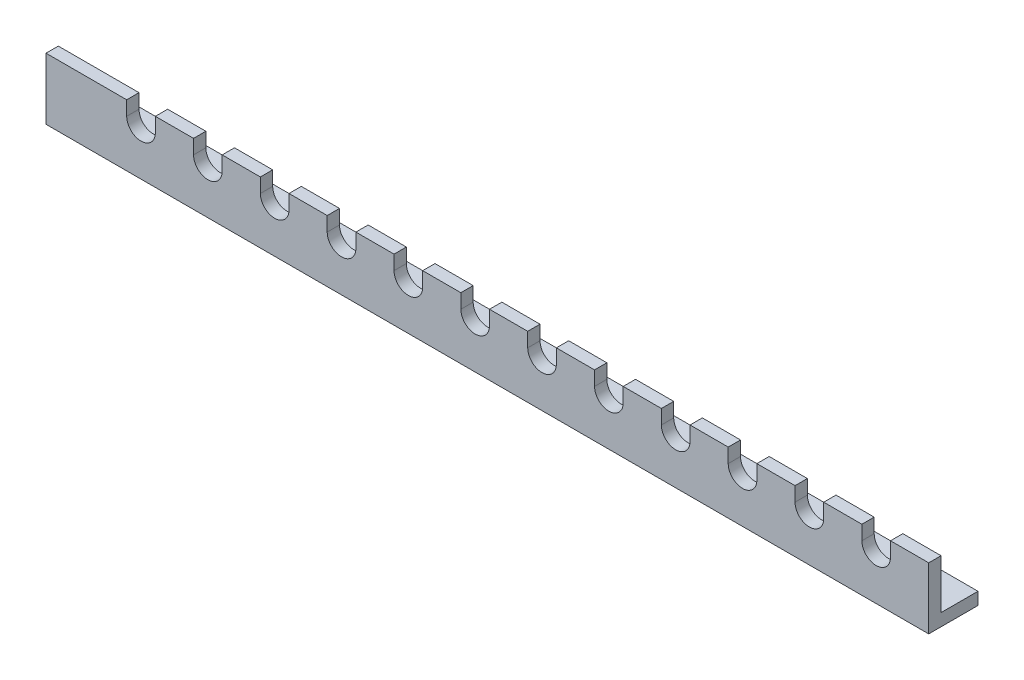
SolidWorks part; units mm, degrees
ref_plane "Front" through (0, 0, 0) normal (0, 0, 1) x (1, 0, 0)
ref_plane "Top" through (0, 0, 0) normal (0, 1, 0) x (1, 0, 0)
ref_plane "Right" through (0, 0, 0) normal (1, 0, 0) x (0, 0, -1)
sketch "Sketch1" plane through (0, 0, 0) normal (0, 0, 1) x (1, 0, 0)
  line L0 (-4.65, 0) -> (-4.65, 4.65)
  line L1 (4.65, 0) -> (4.65, 4.65)
  line L2 (4.65, 4.65) -> (17.05, 4.65)
  line L3 (17.05, 0) -> (17.05, 4.65)
  line L4 (26.35, 0) -> (26.35, 4.65)
  line L5 (26.35, 4.65) -> (38.75, 4.65)
  line L6 (38.75, 0) -> (38.75, 4.65)
  line L7 (48.05, 0) -> (48.05, 4.65)
  line L8 (48.05, 4.65) -> (60.45, 4.65)
  line L9 (60.45, 0) -> (60.45, 4.65)
  line L10 (69.75, 0) -> (69.75, 4.65)
  line L11 (69.75, 4.65) -> (82.15, 4.65)
  line L12 (82.15, 0) -> (82.15, 4.65)
  line L13 (91.45, 0) -> (91.45, 4.65)
  line L14 (91.45, 4.65) -> (103.85, 4.65)
  line L15 (103.85, 0) -> (103.85, 4.65)
  line L16 (113.15, 0) -> (113.15, 4.65)
  line L17 (113.15, 4.65) -> (125.55, 4.65)
  line L18 (125.55, 0) -> (125.55, 4.65)
  line L19 (134.85, 0) -> (134.85, 4.65)
  line L20 (134.85, 4.65) -> (147.25, 4.65)
  line L21 (147.25, 0) -> (147.25, 4.65)
  line L22 (156.55, 0) -> (156.55, 4.65)
  line L23 (156.55, 4.65) -> (168.95, 4.65)
  line L24 (168.95, 0) -> (168.95, 4.65)
  line L25 (178.25, 0) -> (178.25, 4.65)
  line L26 (178.25, 4.65) -> (190.65, 4.65)
  line L27 (190.65, 0) -> (190.65, 4.65)
  line L28 (199.95, 0) -> (199.95, 4.65)
  line L29 (199.95, 4.65) -> (212.35, 4.65)
  line L30 (212.35, 0) -> (212.35, 4.65)
  line L31 (221.65, 0) -> (221.65, 4.65)
  line L32 (221.65, 4.65) -> (234.05, 4.65)
  line L33 (234.05, 0) -> (234.05, 4.65)
  line L34 (243.35, 0) -> (243.35, 4.65)
  line L35 (243.35, 4.65) -> (255.75, 4.65)
  line L36 (-4.65, 4.65) -> (-30.85, 4.65)
  line L37 (-30.85, 4.65) -> (-30.85, -15.35)
  line L38 (-30.85, -15.35) -> (255.75, -15.35)
  line L39 (255.75, -15.35) -> (255.75, 4.65)
  arc A0 (-4.65, 0) -> (4.65, 0) centre (0, 0) ccw
  arc A1 (17.05, 0) -> (26.35, 0) centre (21.7, 0) ccw
  arc A2 (38.75, 0) -> (48.05, 0) centre (43.4, 0) ccw
  arc A3 (60.45, 0) -> (69.75, 0) centre (65.1, 0) ccw
  arc A4 (82.15, 0) -> (91.45, 0) centre (86.8, 0) ccw
  arc A5 (103.85, 0) -> (113.15, 0) centre (108.5, 0) ccw
  arc A6 (125.55, 0) -> (134.85, 0) centre (130.2, 0) ccw
  arc A7 (147.25, 0) -> (156.55, 0) centre (151.9, 0) ccw
  arc A8 (168.95, 0) -> (178.25, 0) centre (173.6, 0) ccw
  arc A9 (190.65, 0) -> (199.95, 0) centre (195.3, 0) ccw
  arc A10 (212.35, 0) -> (221.65, 0) centre (217, 0) ccw
  arc A11 (234.05, 0) -> (243.35, 0) centre (238.7, 0) ccw
  dimension "D1" = 9.3
  dimension "D2" = 21.7
  dimension "D3" = 12
  dimension "D4" = 30.85
  dimension "D5" = 20
extrude "Boss-Extrude1" add sketch "Sketch1" along normal blind 4
sketch "Sketch3" plane through (0, -15.35, 0) normal (0, -1, 0) x (1, 0, 0)
  line L0 (255.75, 4) -> (255.75, 0) construction
  line L1 (-30.85, 0) -> (255.75, 0)
  line L2 (-30.85, 0) -> (-30.85, -12)
  line L3 (-30.85, -12) -> (255.75, -12)
  line L4 (255.75, 0) -> (255.75, -12)
  line L5 (-30.85, 0) -> (255.75, -12) construction
  line L6 (-30.85, -12) -> (255.75, 0) construction
  point P4 (112.45, -6)
  dimension "D1" = 12
extrude "Boss-Extrude2" add sketch "Sketch3" against normal blind 4
sketch "Sketch4" plane through (0, -15.35, 0) normal (0, -1, 0) x (1, 0, 0)
  line L0 (-30.85, 4) -> (255.75, 4) construction
  line L3 (-30.85, 4) -> (-30.85, -12) construction
  line L4 (255.75, 4) -> (255.75, -12) construction
  circle A0 centre (-23.35, -4) radius 1.55
  circle A1 centre (248.25, -4) radius 1.55
  circle A2 centre (-9.85, -4) radius 1.55
  dimension "D1" = 3.1
  dimension "D2" = 8
  dimension "D3" = 7.5
  dimension "D4" = 3.1
  dimension "D5" = 7.5
  dimension "D6" = 3.1
  dimension "D7" = 13.5
extrude "Cut-Extrude1" cut sketch "Sketch4" against normal up to next
